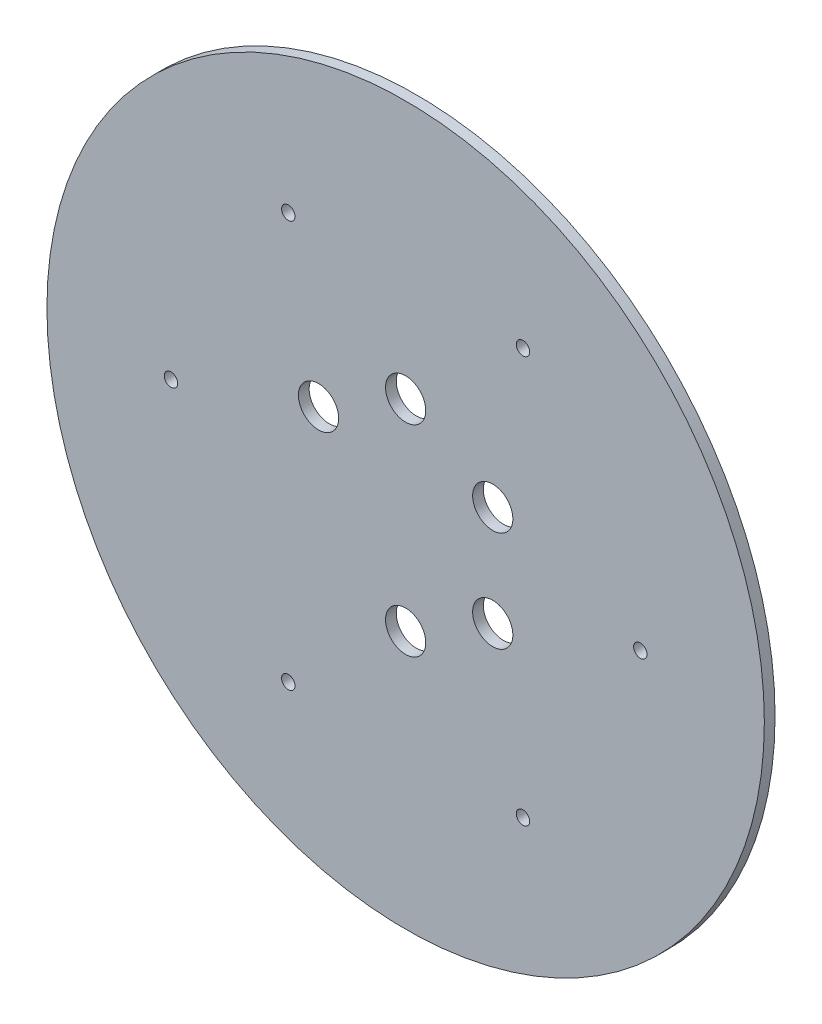
SolidWorks part; units mm, degrees
ref_plane "Plan de face" through (0, 0, 0) normal (0, 0, 1) x (1, 0, 0)
ref_plane "Plan de dessus" through (0, 0, 0) normal (0, 1, 0) x (1, 0, 0)
ref_plane "Plan de droite" through (0, 0, 0) normal (1, 0, 0) x (0, 0, -1)
sketch "Esquisse1" plane through (0, 0, 0) normal (0, 0, 1) x (1, 0, 0)
  circle A12 centre (0, 0) radius 53.5
  line B0 (0, 15) -> (0, -15) construction
  circle B1 centre (35, 0) radius 1
  circle B2 centre (17.5, -30.3109) radius 1
  circle B3 centre (-17.5, -30.3109) radius 1
  circle B4 centre (-35, 0) radius 1
  circle B5 centre (-17.5, 30.3109) radius 1
  circle B6 centre (17.5, 30.3109) radius 1
  circle B7 centre (0, -15) radius 3
  circle B8 centre (12.9904, -7.5) radius 3
  circle B9 centre (12.9904, 7.5) radius 3
  circle B10 centre (0, 15) radius 3
  circle B11 centre (-12.9904, 7.5) radius 3
  dimension "D1" = 107
sketch_block_instance "Bloc1-1"
sketch_block "Bloc1" parameters "D1"=2
extrude "Boss.-Extru.1" add sketch "Esquisse1" along normal blind 1.6
